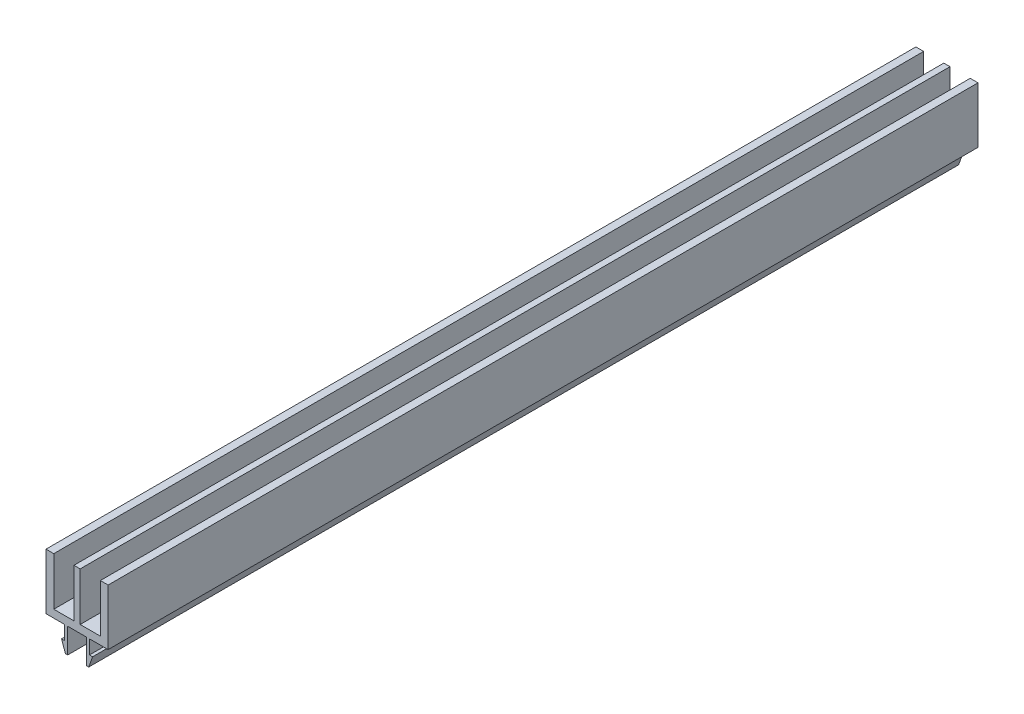
SolidWorks part; units mm, degrees
ref_plane "Plan de face" through (0, 0, 0) normal (0, 0, 1) x (1, 0, 0)
ref_plane "Plan de dessus" through (0, 0, 0) normal (0, 1, 0) x (1, 0, 0)
ref_plane "Plan de droite" through (0, 0, 0) normal (1, 0, 0) x (0, 0, -1)
ref_plane "Plan1" through (0, 0, 50) normal (0, 0, 1) x (1, 0, 0)
sketch "Esquisse1" plane through (0, 0, 50) normal (0, 0, 1) x (1, 0, 0)
  line L0 (-1, 2.5) -> (-7.5, 2.5)
  line L1 (-7.5, 2.5) -> (-7.5, 18)
  line L2 (-7.5, 18) -> (-10, 18)
  line L3 (-10, 18) -> (-10, 0)
  line L4 (-10, 0) -> (-4, 0)
  line L5 (-4, 0) -> (-4, -4.5)
  line L6 (-4, -4.5) -> (-5, -4.5)
  line L7 (-5, -4.5) -> (-3.75, -8)
  line L8 (-3.75, -8) -> (-3, -8)
  line L9 (-3, -8) -> (-3, 0)
  line L10 (-3, 0) -> (3, 0)
  line L11 (3, 0) -> (3, -8)
  line L12 (3, -8) -> (3.75, -8)
  line L13 (3.75, -8) -> (5, -4.5)
  line L14 (5, -4.5) -> (4, -4.5)
  line L15 (4, -4.5) -> (4, 0)
  line L16 (4, 0) -> (10, 0)
  line L17 (10, 0) -> (10, 18)
  line L18 (10, 18) -> (7.5, 18)
  line L19 (7.5, 18) -> (7.5, 2.5)
  line L20 (7.5, 2.5) -> (1, 2.5)
  line L21 (1, 2.5) -> (1, 18)
  line L22 (1, 18) -> (-1, 18)
  line L23 (-1, 18) -> (-1, 2.5)
extrude "Boss.-Extru.1" add sketch "Esquisse1" against normal blind 280
